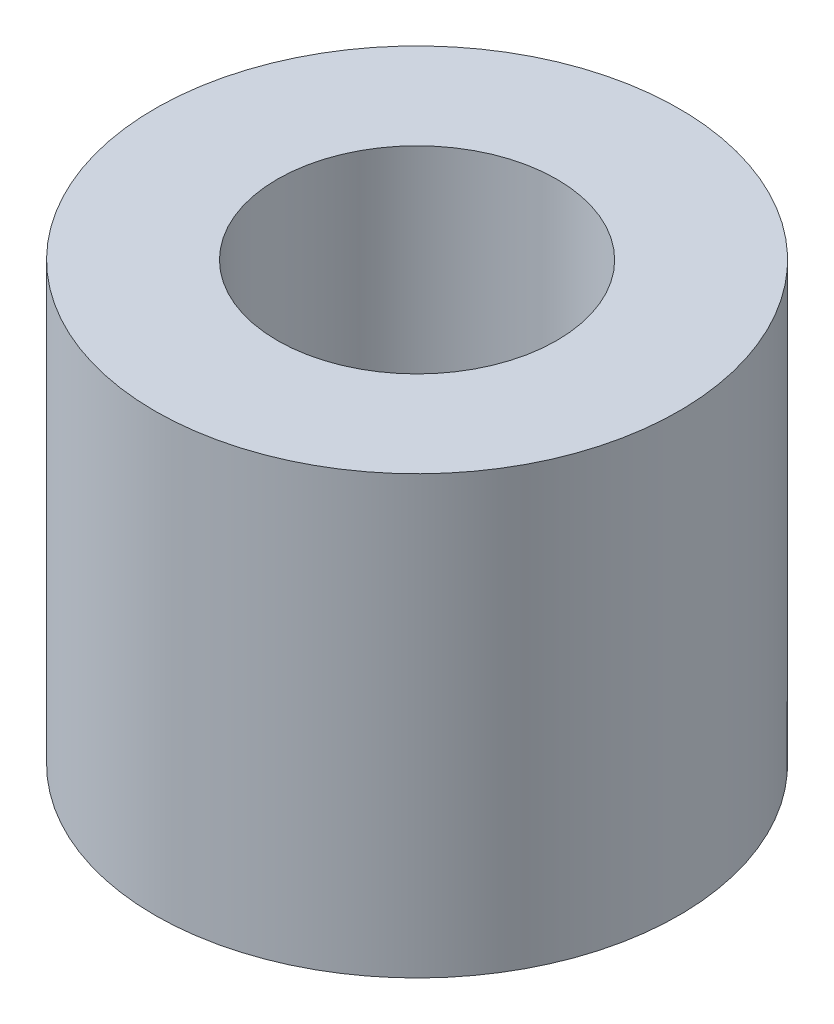
SolidWorks part; units mm, degrees
ref_plane "Přední rovina" through (0, 0, 0) normal (0, 0, 1) x (1, 0, 0)
ref_plane "Horní rovina" through (0, 0, 0) normal (0, 1, 0) x (1, 0, 0)
ref_plane "Pravá rovina" through (0, 0, 0) normal (1, 0, 0) x (0, 0, -1)
sketch "Skica1" plane through (0, 0, 0) normal (0, 1, 0) x (1, 0, 0)
  circle A0 centre (0, 0) radius 1.6
  circle A1 centre (0, 0) radius 3
  dimension "D1" = 3.2
  dimension "D2" = 6
extrude "Přidat vysunutím1" add sketch "Skica1" along normal blind 5
